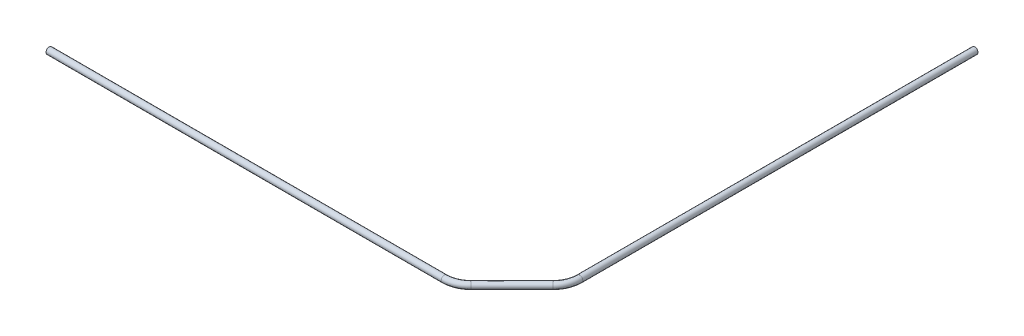
SolidWorks part; units mm, degrees
material "AISI 1020"
ref_plane "Спереди" through (0, 0, 0) normal (0, 0, 1) x (1, 0, 0)
ref_plane "Сверху" through (0, 0, 0) normal (0, 1, 0) x (1, 0, 0)
ref_plane "Справа" through (0, 0, 0) normal (1, 0, 0) x (0, 0, -1)
sketch "Эскиз1" plane through (0, 0, 0) normal (0, 1, 0) x (1, 0, 0)
  line L0 (-850, -18) -> (-108.7767, -18)
  line L1 (-73.4214, -3.3553) -> (3.3553, 73.4214)
  line L2 (18, 108.7767) -> (18, 850)
  line L3 (6, 450) -> (6, 950) construction
  line L4 (-950, -6) -> (-450, -6) construction
  line L5 (-700, 18) -> (-700, 6) construction
  line L6 (-1984.748, 1984.748) -> (1384.748, -1384.748) construction
  arc A0 (3.3553, 73.4214) -> (18, 108.7767) centre (-32, 108.7767) ccw
  arc A1 (-108.7767, -18) -> (-73.4214, -3.3553) centre (-108.7767, 32) ccw
  point P14 (18, 88.066)
  point P17 (-88.066, -18)
  dimension "D5" = 50
  dimension "D1" = 12
  dimension "D2" = 12
  dimension "D3" = 150
  dimension "D4" = 150
ref_plane "Плоскость1" through (-850, 0, 18) normal (1, 0, 0) x (0, 0, -1)
sketch "Эскиз2" plane through (-850, 0, 18) normal (1, 0, 0) x (0, 0, -1)
  circle A0 centre (0, 0) radius 6
  dimension "D1" = 12
sweep "По траектории1" add profiles "Эскиз2" path "Эскиз1"
